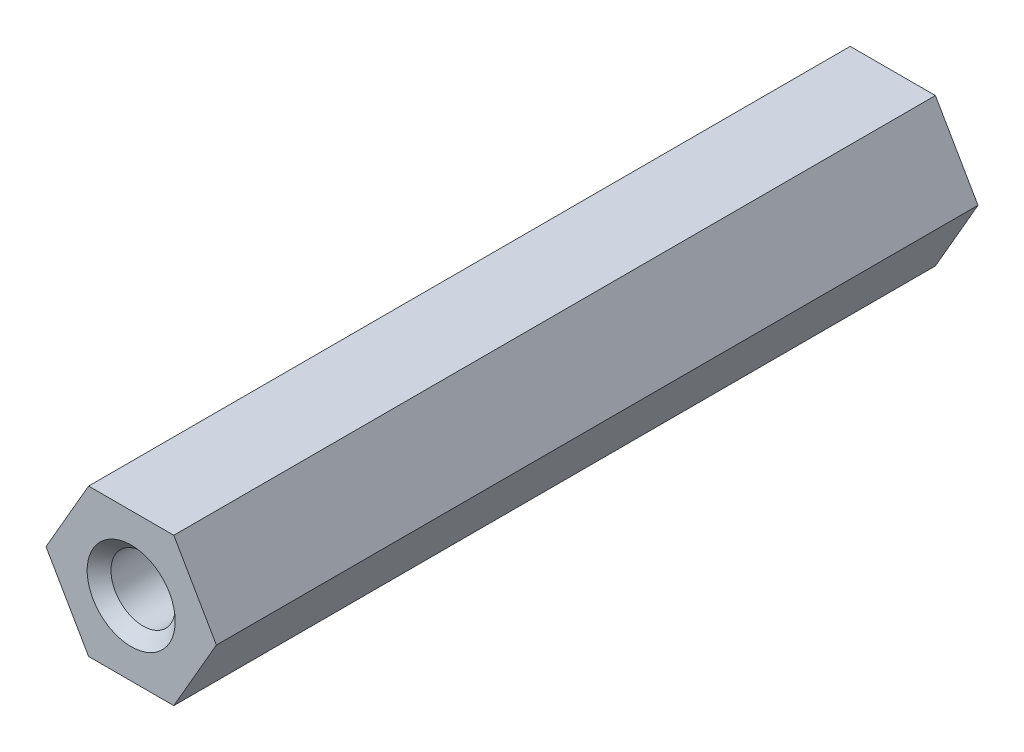
SolidWorks part; units mm, degrees
ref_plane "Front" through (0, 0, 0) normal (0, 0, 1) x (1, 0, 0)
ref_plane "Top" through (0, 0, 0) normal (0, 1, 0) x (1, 0, 0)
ref_plane "Right" through (0, 0, 0) normal (1, 0, 0) x (0, 0, -1)
ref_plane "Plane1" through (0, 0, 36.2395) normal (0, 0, 1) x (1, 0, 0)
sketch "Sketch1" plane through (0, 0, 36.2395) normal (0, 0, 1) x (1, 0, 0)
  line L0 (-24.4571, -8.0145) -> (-26.2469, -4.9145)
  line L1 (-26.2469, -4.9145) -> (-29.8264, -4.9145)
  line L2 (-29.8264, -4.9145) -> (-31.6162, -8.0145)
  line L3 (-31.6162, -8.0145) -> (-29.8264, -11.1145)
  line L4 (-29.8264, -11.1145) -> (-26.2469, -11.1145)
  line L5 (-26.2469, -11.1145) -> (-24.4571, -8.0145)
extrude "Boss-Extrude1" add sketch "Sketch1" against normal blind 32
hole_wizard "Ø2.7 (2.7) Diameter Hole1" positions "Sketch3" profile "Sketch2" hole size "Ø2.7" standard "ANSI Metric"
sketch "Sketch3" plane through (0, 0, 36.2395) normal (0, 0, 1) x (1, 0, 0)
  point P0 (-28.0367, -8.0145)
sketch "Sketch2" plane through (-28.0367, -8.0145, 36.2395) normal (1, 0, 0) x (0, -1, 0)
  line L0 (0, 0) -> (0, 32)
  line L1 (0, 32) -> (1.35, 32)
  line L2 (1.35, 32) -> (1.35, 0)
  line L5 (1.35, 0) -> (0, 0)
  line L11 (0, -6.35) -> (0, 107.95) construction
  dimension "Thru Hole Dia." = 2.7
  dimension "Thru Hole Depth" = 32
chamfer "Chamfer1" distance 0.5 angle 45 2 edges at (-26.6867, -8.0145, 4.2395) (-26.6867, -8.0145, 36.2395)
